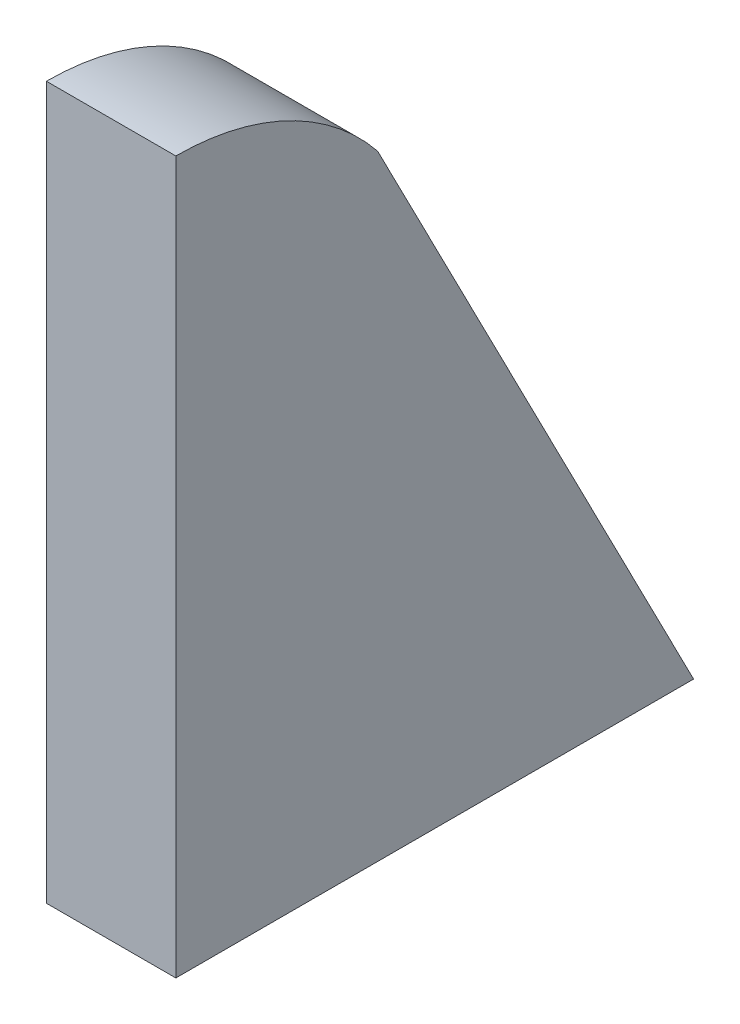
SolidWorks part; units mm, degrees
ref_plane "Front Plane" through (0, 0, 0) normal (0, 0, 1) x (1, 0, 0)
ref_plane "Top Plane" through (0, 0, 0) normal (0, 1, 0) x (1, 0, 0)
ref_plane "Right Plane" through (0, 0, 0) normal (1, 0, 0) x (0, 0, -1)
sketch "Sketch2" plane through (0, 0, 0) normal (1, 0, 0) x (0, 0, -1)
  line L0 (0, 0) -> (40, 0)
  line L1 (0, 0) -> (0, 55)
  line L2 (40, 0) -> (15.5853, 47.5339)
  arc A1 (0, 55) -> (15.5853, 47.5339) centre (0, 35) cw
  point P6 (8.6407, 53.0371)
  dimension "D1" = 40
  dimension "D2" = 55
extrude "Boss-Extrude1" add sketch "Sketch2" along normal blind 10
